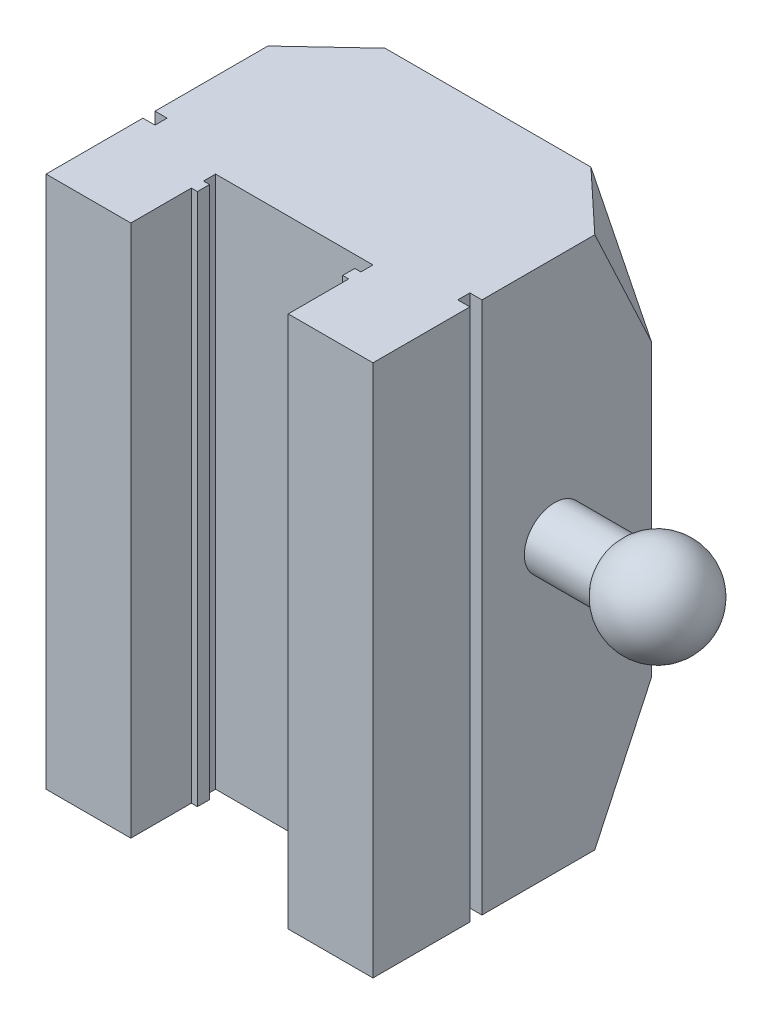
SolidWorks part; units mm, degrees
ref_plane "前基準面" through (0, 0, 0) normal (0, 0, 1) x (1, 0, 0)
ref_plane "上基準面" through (0, 0, 0) normal (0, 1, 0) x (1, 0, 0)
ref_plane "右基準面" through (0, 0, 0) normal (1, 0, 0) x (0, 0, -1)
sketch "草圖1" plane through (0, 0, 0) normal (0, 1, 0) x (1, 0, 0)
  line L0 (0, 0) -> (0, 11.8113) construction
  line L1 (-13.5, 0) -> (-6.5, 0)
  line L2 (13.5, 0) -> (13.5, 8)
  line L3 (13.5, 8) -> (12.5, 8)
  line L4 (12.5, 8) -> (12.5, 9)
  line L5 (12.5, 9) -> (13.5, 9)
  line L6 (13.5, 9) -> (13.5, 23)
  line L7 (13.5, 23) -> (-13.5, 23)
  line L8 (-13.5, 9) -> (-13.5, 23)
  line L9 (-12.5, 9) -> (-13.5, 9)
  line L10 (-12.5, 8) -> (-12.5, 9)
  line L11 (-13.5, 8) -> (-12.5, 8)
  line L12 (-13.5, 0) -> (-13.5, 8)
  line L13 (6.5, 0) -> (6.5, 5)
  line L14 (6.5, 7) -> (-6.5, 7)
  line L15 (-6.5, 6) -> (-6.5, 7)
  line L16 (6.5, 5) -> (6, 5)
  line L17 (6, 5) -> (6, 6)
  line L18 (6, 6) -> (6.5, 6)
  line L19 (6.5, 6) -> (6.5, 7)
  line L20 (-6, 6) -> (-6.5, 6)
  line L21 (-6, 5) -> (-6, 6)
  line L22 (6.5, 0) -> (13.5, 0)
  line L23 (-6.5, 5) -> (-6, 5)
  line L24 (-6.5, 0) -> (-6.5, 5)
  point P11 (0, 23)
  point P28 (0, 7)
  dimension "D1" = 8
  dimension "D2" = 1
  dimension "D3" = 23
  dimension "D4" = 27
  dimension "D5" = 1
  dimension "D6" = 5
  dimension "D7" = 1
  dimension "D8" = 1
  dimension "D9" = 13
  dimension "D10" = 0.5
extrude "填料-伸長1" add sketch "草圖1" along normal blind 44
sketch "草圖2" plane through (0, 0, -23) normal (0, 0, -1) x (-1, 0, 0)
  line L0 (-13.5, 44) -> (-8.5, 44)
  line L1 (-13.5, 44) -> (13.5, 44) construction
  line L2 (-8.5, 44) -> (-13.5, 34)
  line L3 (-13.5, 44) -> (-13.5, 0) construction
  line L4 (-13.5, 34) -> (-13.5, 44)
  dimension "D1" = 5
  dimension "D2" = 10
sketch "草圖3" plane through (13.5, 0, 0) normal (1, 0, 0) x (0, 0, -1)
  line L0 (23, 34) -> (18.3179, 44)
  line L1 (23, 34) -> (23, 44) construction
  line L2 (9, 44) -> (23, 44) construction
sweep "除料-掃出1" cut profiles "草圖2" path "草圖3"
mirror "鏡射1" about plane through (0, 0, 0) normal (1, 0, 0) of "除料-掃出1"
ref_plane "平面1" through (0, 22, 0) normal (0, -1, 0) x (-1, 0, 0)
mirror "鏡射2" about plane through (0, 22, 0) normal (0, -1, 0) of "鏡射1", "除料-掃出1"
sketch "草圖4" plane through (0, 0, 0) normal (1, 0, 0) x (0, 0, -1)
  line L0 (23, 34) -> (23, 10) construction
  line L1 (9, 44) -> (18.3179, 44) construction
  circle A0 centre (15, 24) radius 2.5
  dimension "D1" = 8
  dimension "D2" = 20
  dimension "D3" = 5
extrude "填料-伸長2" add sketch "草圖4" along normal mid plane 44
sketch "草圖5" plane through (22, 0, 0) normal (1, 0, 0) x (0, 0, -1)
  line L0 (15, 24) -> (15, 17.8238) construction
  line L1 (15, 24) -> (15, 31.7132) construction
  line L2 (15, 28) -> (15, 20)
  arc A0 (15, 20) -> (15, 28) centre (15, 24) ccw
  dimension "D1" = 8
revolve "旋轉1" add sketch "草圖5" angle 360 about L1
mirror "鏡射3" about plane through (0, 0, 0) normal (1, 0, 0) of "旋轉1"
